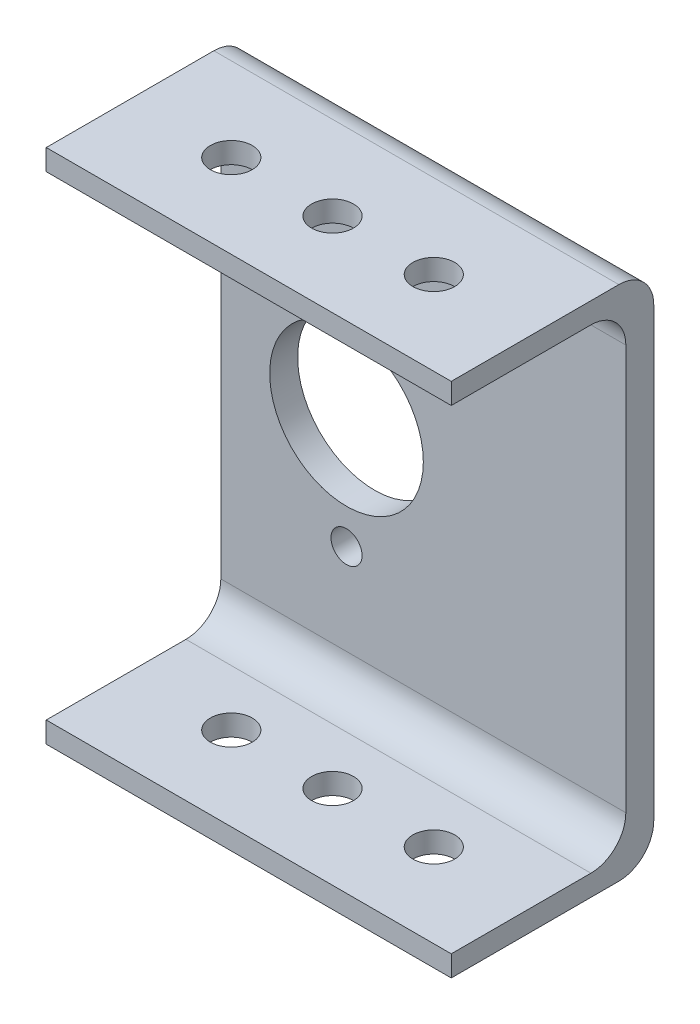
SolidWorks part; units mm, degrees
ref_plane "Front Plane" through (0, 0, 0) normal (0, 0, 1) x (1, 0, 0)
ref_plane "Top Plane" through (0, 0, 0) normal (0, 1, 0) x (1, 0, 0)
ref_plane "Right Plane" through (0, 0, 0) normal (1, 0, 0) x (0, 0, -1)
sketch "Sketch3" plane through (0, 0, 0) normal (0, 0, 1) x (1, 0, 0)
  line L5 (39, 0) -> (-19, 0) construction
  line L8 (-19, 37) -> (39, 37)
  line L12 (-19, -37) -> (39, -37)
  line L14 (-19, 37) -> (-19, 0)
  line L15 (-19, 0) -> (-19, -37)
  line L16 (39, -37) -> (39, 0)
  line L17 (39, 0) -> (39, 37)
  circle A0 centre (-1, 0) radius 11
  dimension "D1" = 22
  dimension "D2" = 37
  dimension "D3" = 58
extrude "Boss-Extrude1" add sketch "Sketch3" along normal blind 4
sketch "Sketch5" plane through (0, 0, 4) normal (0, 0, 1) x (1, 0, 0)
  line L0 (39, -37) -> (39, 37) construction
  line L1 (-19, 37) -> (39, 37)
  line L2 (-19, 37) -> (-19, 34)
  line L3 (-19, 34) -> (39, 34)
  line L4 (39, 37) -> (39, 34)
  line L5 (-19, 37) -> (-19, -37) construction
  line L6 (39, -37) -> (-19, -37)
  line L7 (39, -37) -> (39, -34)
  line L8 (39, -34) -> (-19, -34)
  line L9 (-19, -37) -> (-19, -34)
  dimension "D1" = 3
extrude "Boss-Extrude2" add sketch "Sketch5" along normal blind 25
fillet "Fillet1" radius 5 4 edges at (10, -34, 4) (10, 34, 4) (10, 37, 0) (10, -37, 0)
sketch "Sketch6" plane through (0, -37, 0) normal (0, -1, 0) x (1, 0, 0)
  line L0 (39, 17) -> (24.5, 17) construction
  line L1 (39, 29) -> (39, 5) construction
  line L2 (24.5, 17) -> (10, 17) construction
  line L3 (10, 17) -> (-4.5, 17) construction
  line L4 (-4.5, 17) -> (-19, 17) construction
  line L5 (-19, 29) -> (-19, 5) construction
  line L7 (39, 5) -> (39, 17) construction
  line L8 (39, 17) -> (39, 29) construction
  circle A0 centre (24.5, 17) radius 3
  circle A1 centre (-4.5, 17) radius 3
  circle A2 centre (10, 17) radius 3
extrude "Cut-Extrude1" cut sketch "Sketch6" against normal through all
sketch "Sketch7" plane through (0, 0, 0) normal (0, 0, -1) x (-1, 0, 0)
  circle A0 centre (1, -16) radius 2.225
  circle A1 centre (1, 16) radius 2.225
extrude "Cut-Extrude2" cut sketch "Sketch7" against normal through all
